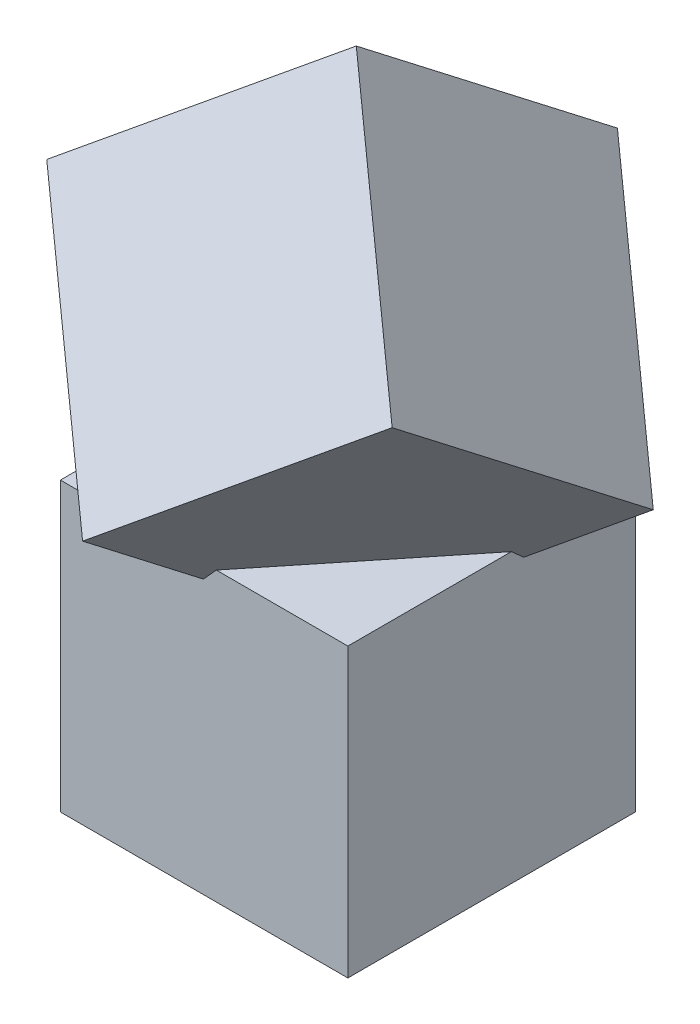
SolidWorks part; units mm, degrees
ref_plane "Front Plane" through (0, 0, 0) normal (0, 0, 1) x (1, 0, 0)
ref_plane "Top Plane" through (0, 0, 0) normal (0, 1, 0) x (1, 0, 0)
ref_plane "Right Plane" through (0, 0, 0) normal (1, 0, 0) x (0, 0, -1)
sketch "Sketch1" plane through (0, 0, 0) normal (0, 1, 0) x (1, 0, 0)
  line L0 (-38.1, -38.1) -> (38.1, 38.1) construction
  line L1 (-38.1, -38.1) -> (38.1, -38.1)
  line L2 (-38.1, -38.1) -> (-38.1, 38.1)
  line L3 (-38.1, 38.1) -> (38.1, 38.1)
  line L4 (38.1, -38.1) -> (38.1, 38.1)
  dimension "D1" = 76.2
  dimension "D2" = 76.2
extrude "Boss-Extrude1" add sketch "Sketch1" along normal blind 76.2
move or copy body "Body-Move/Copy1" bodies to move or copy 101 copy yes number of copies 1 rotation origin (5.4374, 44.1537, -2.5209) rotation axis (-0.671, 0.1244, 0.7309) rotation angle 55.414
move or copy body "Body-Move/Copy2" bodies to move or copy 102 copy no translate (0, 75.0906, 0) parameters "D1"=0, "D2"=75.0906, "D3"=0
